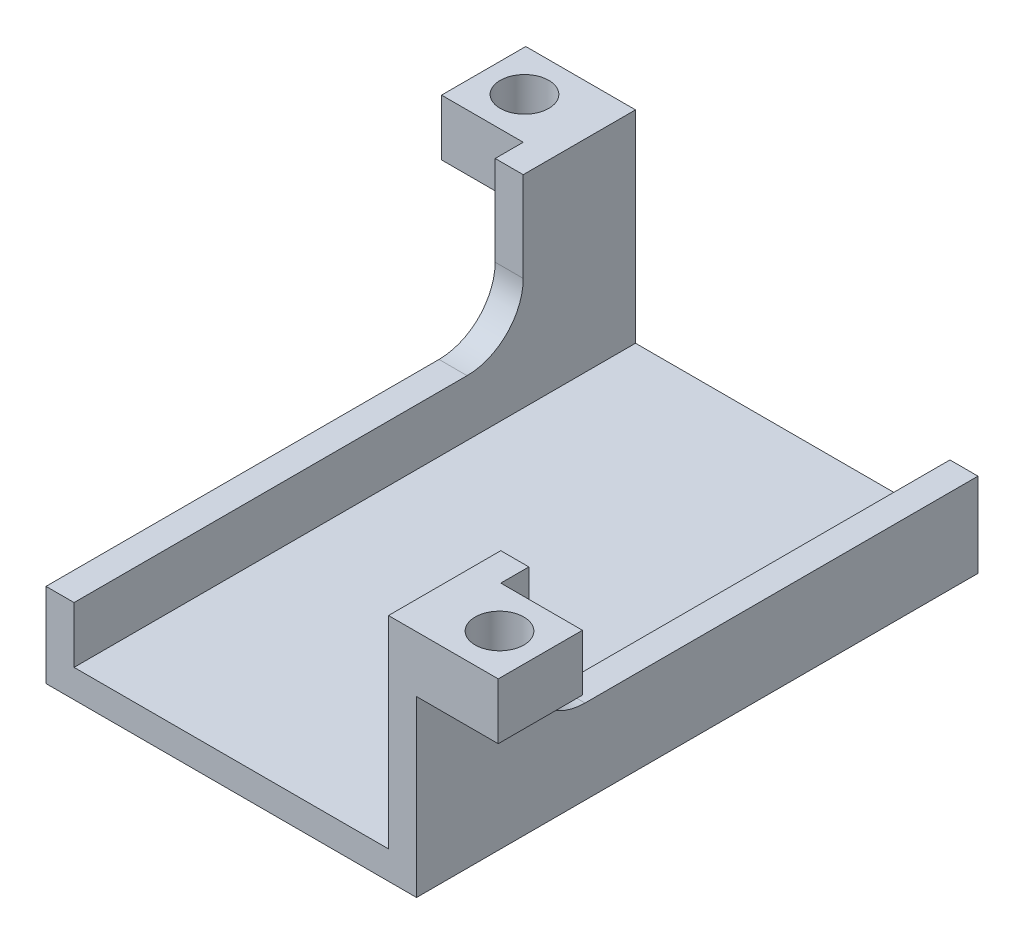
SolidWorks part; units mm, degrees
ref_plane "Front Plane" through (0, 0, 0) normal (0, 0, 1) x (1, 0, 0)
ref_plane "Top Plane" through (0, 0, 0) normal (0, 1, 0) x (1, 0, 0)
ref_plane "Right Plane" through (0, 0, 0) normal (1, 0, 0) x (0, 0, -1)
sketch "Sketch1" plane through (0, 0, 0) normal (0, 1, 0) x (1, 0, 0)
  line L1 (-20.955, -31.75) -> (20.955, -31.75)
  line L2 (-20.955, -31.75) -> (-20.955, 31.75)
  line L3 (-20.955, 31.75) -> (20.955, 31.75)
  line L4 (20.955, -31.75) -> (20.955, 31.75)
  line L5 (-20.955, -31.75) -> (20.955, 31.75) construction
  line L6 (-20.955, 31.75) -> (20.955, -31.75) construction
  point P0 (0, 0)
  dimension "D1" = 63.5
  dimension "D2" = 41.91
extrude "Boss-Extrude1" add sketch "Sketch1" along normal blind 3.175
sketch "Sketch2" plane through (0, 3.175, 0) normal (0, 1, 0) x (1, 0, 0)
  line L0 (-20.955, -31.75) -> (20.955, -31.75) construction
  line L1 (-20.955, 31.75) -> (-17.78, 31.75)
  line L2 (-20.955, 31.75) -> (-20.955, -31.75)
  line L3 (-20.955, -31.75) -> (-17.78, -31.75)
  line L4 (-17.78, 31.75) -> (-17.78, -31.75)
  line L6 (20.955, 31.75) -> (17.78, 31.75)
  line L7 (20.955, 31.75) -> (20.955, -31.75)
  line L8 (20.955, -31.75) -> (17.78, -31.75)
  line L9 (17.78, 31.75) -> (17.78, -31.75)
  dimension "D1" = 35.56
extrude "Boss-Extrude2" add sketch "Sketch2" along normal blind 6.35
sketch "Sketch5" plane through (0, 9.525, 0) normal (0, 1, 0) x (1, 0, 0)
  line L0 (17.78, 31.75) -> (17.78, -31.75) construction
  line L1 (20.955, 31.75) -> (17.78, 31.75)
  line L2 (20.955, 31.75) -> (20.955, 19.05)
  line L3 (20.955, 19.05) -> (17.78, 19.05)
  line L4 (17.78, 31.75) -> (17.78, 19.05)
  line L5 (-17.78, -31.75) -> (-17.78, 31.75) construction
  line L6 (-20.955, -31.75) -> (-17.78, -31.75)
  line L7 (-20.955, -31.75) -> (-20.955, -19.05)
  line L8 (-20.955, -19.05) -> (-17.78, -19.05)
  line L9 (-17.78, -31.75) -> (-17.78, -19.05)
  dimension "D1" = 12.7
extrude "Boss-Extrude4" add sketch "Sketch5" along normal blind 16.51
sketch "Sketch6" plane through (0, 26.035, 0) normal (0, 1, 0) x (1, 0, 0)
  line L0 (20.955, -31.75) -> (20.955, 31.75) construction
  line L1 (27.8832, 22.9875) -> (30.1926, 26.9875) construction
  line L2 (30.1926, 26.9875) -> (27.8832, 30.9875) construction
  line L3 (27.8832, 30.9875) -> (23.2644, 30.9875) construction
  line L4 (23.2644, 30.9875) -> (20.955, 26.9875) construction
  line L5 (20.955, 26.9875) -> (23.2644, 22.9875) construction
  line L6 (23.2644, 22.9875) -> (27.8832, 22.9875) construction
  line L7 (-20.955, -31.75) -> (-30.1926, -31.75)
  line L8 (20.955, 31.75) -> (30.1926, 31.75)
  line L9 (20.955, 31.75) -> (20.955, 22.225)
  line L10 (20.955, 22.225) -> (30.1926, 22.225)
  line L11 (30.1926, 31.75) -> (30.1926, 22.225)
  line L12 (-20.955, -31.75) -> (-20.955, -22.225)
  line L13 (-20.955, -22.225) -> (-30.1926, -22.225)
  line L14 (-30.1926, -31.75) -> (-30.1926, -22.225)
  line L15 (-27.8832, -22.9875) -> (-30.1926, -26.9875) construction
  line L16 (-30.1926, -26.9875) -> (-27.8832, -30.9875) construction
  line L17 (-27.8832, -30.9875) -> (-23.2644, -30.9875) construction
  line L18 (-23.2644, -30.9875) -> (-20.955, -26.9875) construction
  line L19 (-20.955, -26.9875) -> (-23.2644, -22.9875) construction
  line L20 (-23.2644, -22.9875) -> (-27.8832, -22.9875) construction
  line L21 (-20.955, 31.75) -> (-20.955, -31.75) construction
  circle A0 centre (25.5738, 26.9875) radius 4 construction
  circle A1 centre (25.5738, 26.9875) radius 2.75
  circle A2 centre (-25.5738, -26.9875) radius 2.75
  circle A3 centre (-25.5738, -26.9875) radius 4 construction
  point P17 (-31.708, -41.7368)
  point P18 (0, 0)
  point P31 (0, 0)
  dimension "D1" = 8
  dimension "D2" = 5.5
  dimension "D3" = 9.2376
  dimension "D4" = 9.525
  dimension "D5" = 2
extrude "Boss-Extrude5" add sketch "Sketch6" against normal blind 6.35
fillet "Fillet2" radius 6.35 2 edges at (19.3675, 9.525, -19.05) (-19.3675, 9.525, 19.05)
mirror "Mirror1" about plane through (-30.1926, 19.685, 31.75) normal (-1, 0, 0) of bodies 106
delete or keep bodies "Body-Delete/Keep 1" type delete bodies bodies 106
